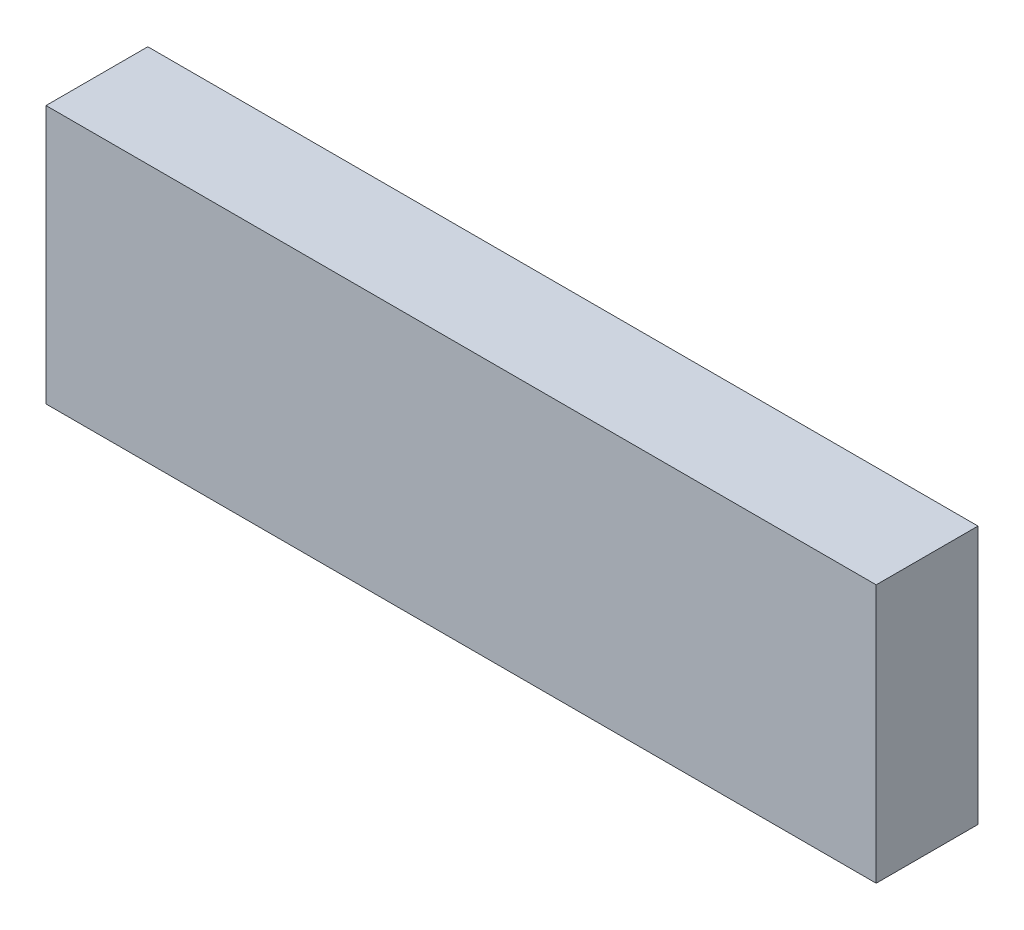
SolidWorks part; units mm, degrees
ref_plane "Front Plane" through (0, 0, 0) normal (0, 0, 1) x (1, 0, 0)
ref_plane "Top Plane" through (0, 0, 0) normal (0, 1, 0) x (1, 0, 0)
ref_plane "Right Plane" through (0, 0, 0) normal (1, 0, 0) x (0, 0, -1)
sketch "Sketch1" plane through (0, 0, 0) normal (0, 1, 0) x (1, 0, 0)
  line L1 (0, 0) -> (106, 0)
  line L2 (0, 0) -> (0, 13)
  line L3 (0, 13) -> (106, 13)
  line L4 (106, 0) -> (106, 13)
extrude "Boss-Extrude1" add sketch "Sketch1" along normal blind 33
